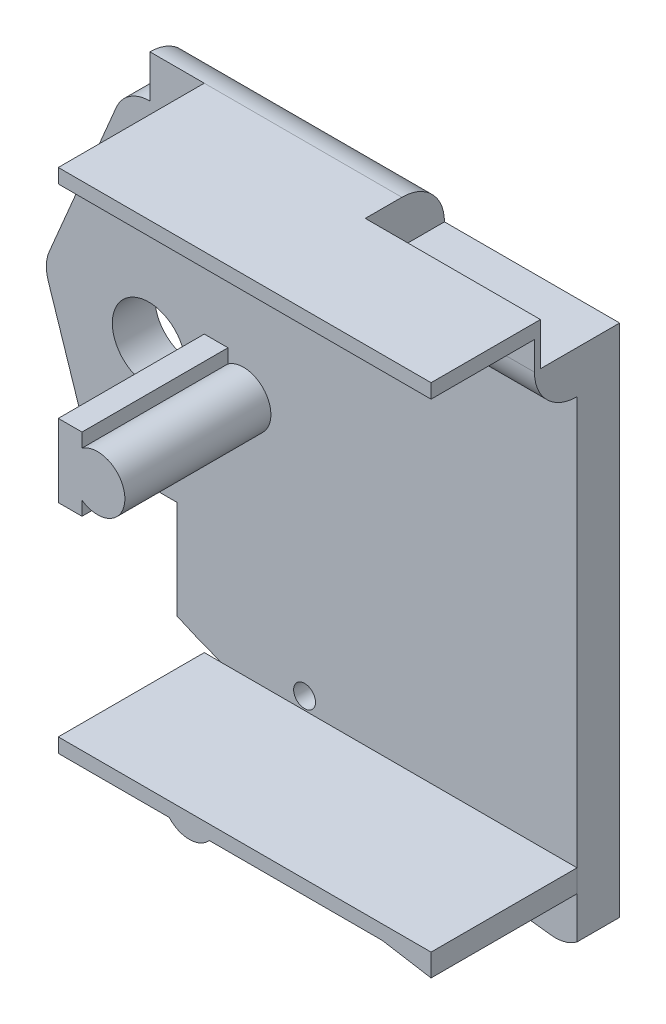
SolidWorks part; units mm, degrees
ref_plane "Спереди" through (0, 0, 0) normal (0, 0, 1) x (1, 0, 0)
ref_plane "Сверху" through (0, 0, 0) normal (0, 1, 0) x (1, 0, 0)
ref_plane "Справа" through (0, 0, 0) normal (1, 0, 0) x (0, 0, -1)
sketch "Эскиз2" plane through (0, 0, 0) normal (0, 0, 1) x (1, 0, 0)
  line L0 (-56.0468, 57.8448) -> (-56.0468, -75.1952)
  line L1 (-186.2888, 51.7421) -> (-204.676, 8.2939)
  line L4 (-193.5028, -33.6946) -> (-169.7062, -33.6946)
  line L5 (-169.7062, -33.6946) -> (-169.7062, -60.6352)
  line L24 (-193.5028, -33.6946) -> (-204.9691, 1.2814)
  line L27 (-177.0796, 57.8448) -> (-56.0468, 57.8448)
  arc A1 (-204.676, 8.2939) -> (-204.9691, 1.2814) centre (-195.4667, 4.3966) ccw
  arc A2 (-186.2888, 51.7421) -> (-177.0796, 57.8448) centre (-177.0796, 47.8448) cw
  arc A3 (-67.1233, -85.137) -> (-56.0468, -75.1952) centre (-66.0468, -75.1952) ccw
  circle A15 centre (-134.7062, -62.1552) radius 3
  spline S1 degree 3 poles (-169.7062, -60.6352) (-159.6635, -65.3294) (-148.3339, -68.8072) (-114.3227, -77.8089) (-90.3681, -82.6201) (-67.1233, -85.137) knots 0.055135 0.055135 0.055135 0.055135 0.172676 0.181905 0.429838 0.429838 0.429838 0.429838
  dimension "D1" = 10
  dimension "D2" = 10
ref_plane "?????25" through (0, 0, 53) normal (0, 0, 1) x (1, 0, 0)
sketch "Эскиз3" plane through (0, 0, 53) normal (0, 0, 1) x (-1, 0, 0)
  line L0 (54.8754, -65.5997) -> (54.8754, -69.5161)
  line L1 (54.8754, 72.6089) -> (54.8754, 65.5997)
  line L3 (155.6874, 10.0166) -> (162.1868, 10.0166)
  line L4 (155.6874, 10.0166) -> (155.6874, 6.196)
  line L6 (155.6874, -9.9834) -> (162.1868, -9.9834)
  line L8 (162.1868, 10.0166) -> (162.1868, -9.9834)
  line L10 (155.6874, -6.1628) -> (155.6874, -9.9834)
  line L15 (204.9076, -65.5997) -> (54.8754, -65.5997)
  line L16 (204.6318, -69.5161) -> (204.9076, -65.5997)
  line L17 (204.6318, -69.5161) -> (54.8754, -69.5161)
  line L19 (133.5844, 65.5997) -> (54.8754, 65.5997)
  line L20 (204.9076, 65.5997) -> (133.5844, 65.5997)
  line L21 (204.6318, 69.5161) -> (204.9076, 65.5997)
  line L22 (131.7963, 69.5161) -> (204.6318, 69.5161)
  line L23 (73.4325, 69.5161) -> (120.8114, 69.5161)
  line L25 (73.4325, 69.5161) -> (54.8754, 72.6089)
  arc A0 (155.6874, 6.196) -> (155.6874, -6.1628) centre (151.4371, 0.0166) ccw
  arc A7 (120.8114, 69.5161) -> (131.7963, 69.5161) centre (126.3039, 64.642) cw
  point P4 (158.9371, 0.0166)
  dimension "D1" = 15
  dimension "D2" = 20
extrude "Бобышка-Вытянуть1" add sketch "Эскиз3" against normal blind 40
extrude "Бобышка-Вытянуть2" add sketch "Эскиз2" along normal blind 13 separate body
sketch "Эскиз4" plane through (-56.0468, 0, 0) normal (1, 0, 0) x (0, 0, -1)
  line L0 (-21.7224, 65.5997) -> (-13, 65.5997)
  line L2 (-13, 65.5997) -> (-13, 57.8448)
  line L3 (-13, 57.8448) -> (-1.3287, 57.8448)
  arc A0 (-1.3287, 57.8448) -> (-21.7224, 65.5997) centre (-13, 57.8448) ccw
extrude "Бобышка-Вытянуть3" add sketch "Эскиз4" against normal up to vertex (148.8609 mm away)
sketch "Эскиз5" plane through (-56.0468, 0, 0) normal (1, 0, 0) x (0, 0, -1)
  line L0 (-13, 69.5161) -> (-24.6713, 69.5161)
  line L1 (-13, 69.5161) -> (-53, 69.5161) construction
  line L2 (-24.6713, 69.5161) -> (-24.6713, 57.8448)
  arc A0 (-24.6713, 57.8448) -> (-13, 69.5161) centre (-13, 57.8448) ccw
extrude "Бобышка-Вытянуть4" add sketch "Эскиз5" against normal blind 55
sketch "Эскиз6" plane through (-56.0468, 0, 0) normal (1, 0, 0) x (0, 0, -1)
  line L0 (-23.0301, 57.8448) -> (-23.0301, 69.5161)
  line L1 (-13, 69.5161) -> (-53, 69.5161) construction
  line L2 (-23.0301, 69.5161) -> (0, 69.5161)
  line L3 (0, 69.5161) -> (0, 57.8448)
  line L4 (0, 57.8448) -> (-23.0301, 57.8448)
extrude "Вырез-Вытянуть1" cut sketch "Эскиз6" against normal blind 52
sketch "Эскиз7" plane through (0, 0, 13) normal (0, 0, -1) x (-1, 0, 0)
  line L1 (54.8754, 69.5161) -> (56.0468, 69.5161)
  line L2 (54.8754, 69.5161) -> (54.8754, 65.5997)
  line L3 (54.8754, 65.5997) -> (56.0468, 65.5997)
  line L4 (56.0468, 69.5161) -> (56.0468, 65.5997)
extrude "Вырез-Вытянуть2" cut sketch "Эскиз7" against normal blind 52
sketch "Эскиз8" plane through (0, 0, 13) normal (0, 0, -1) x (-1, 0, 0)
  line L0 (56.0468, -75.1952) -> (56.0468, 57.8448) construction
  line L1 (54.8754, -65.5997) -> (56.0468, -65.5997)
  line L2 (54.8754, -65.5997) -> (54.8754, -72.6441)
  line L3 (54.8754, -72.6441) -> (56.0468, -72.6441)
  line L4 (56.0468, -65.5997) -> (56.0468, -72.6441)
extrude "Вырез-Вытянуть3" cut sketch "Эскиз8" against normal blind 52
sketch "Эскиз9" plane through (0, 0, 53) normal (0, 0, 1) x (1, 0, 0)
  line L0 (-162.1868, 9.8124) -> (-162.1868, 78.3892)
  line L1 (-162.1868, 9.9834) -> (-162.1868, -10.0166) construction
  line L2 (-162.1868, 78.3892) -> (-213.7657, 78.3892)
  line L3 (-213.7657, 78.3892) -> (-213.7657, -81.2546)
  line L4 (-213.7657, -81.2546) -> (-162.1868, -81.2546)
  line L5 (-162.1868, -81.2546) -> (-162.1868, 9.8124)
extrude "Вырез-Вытянуть4" cut sketch "Эскиз9" against normal blind 40
sketch "Эскиз11" plane through (-56.0468, 0, 0) normal (1, 0, 0) x (0, 0, -1)
  line L0 (-1.3287, 57.8448) -> (0, 57.8448)
  line L1 (0, 57.8448) -> (0, -90.6618)
  line L2 (0, -90.6618) -> (-1.3287, -90.6618)
  line L3 (-1.3287, -90.6618) -> (-1.3287, 57.8448)
extrude "Вырез-Вытянуть5" cut sketch "Эскиз11" against normal blind 160
sketch "Эскиз12" plane through (0, 0, 1.3287) normal (0, 0, -1) x (-1, 0, 0)
  line L1 (56.0468, 69.5161) -> (60.0468, 69.5161)
  line L2 (56.0468, 69.5161) -> (56.0468, -92.7652)
  line L3 (56.0468, -92.7652) -> (60.0468, -92.7652)
  line L4 (60.0468, 69.5161) -> (60.0468, -92.7652)
  dimension "D1" = 4
extrude "Вырез-Вытянуть6" cut sketch "Эскиз12" against normal blind 160
sketch "Эскиз13" plane through (0, 0, 1.3287) normal (0, 0, -1) x (-1, 0, 0)
  circle A0 centre (177.3858, -0.0057) radius 10
extrude "Вырез-Вытянуть8" cut sketch "Эскиз13" against normal blind 32
sketch "Эскиз14" plane through (0, 0, 13) normal (0, 0, 1) x (1, 0, 0)
  line L0 (-177.0796, 57.8448) -> (-177.0796, 69.5161)
  line L1 (-204.9076, 69.5161) -> (-162.1868, 69.5161) construction
  line L2 (-177.0796, 69.5161) -> (-204.9076, 69.5161)
  line L3 (-204.9076, 69.5161) -> (-204.9076, 57.8448)
  line L4 (-204.9076, 57.8448) -> (-177.0796, 57.8448)
extrude "Вырез-Вытянуть9" cut sketch "Эскиз14" against normal blind 18
